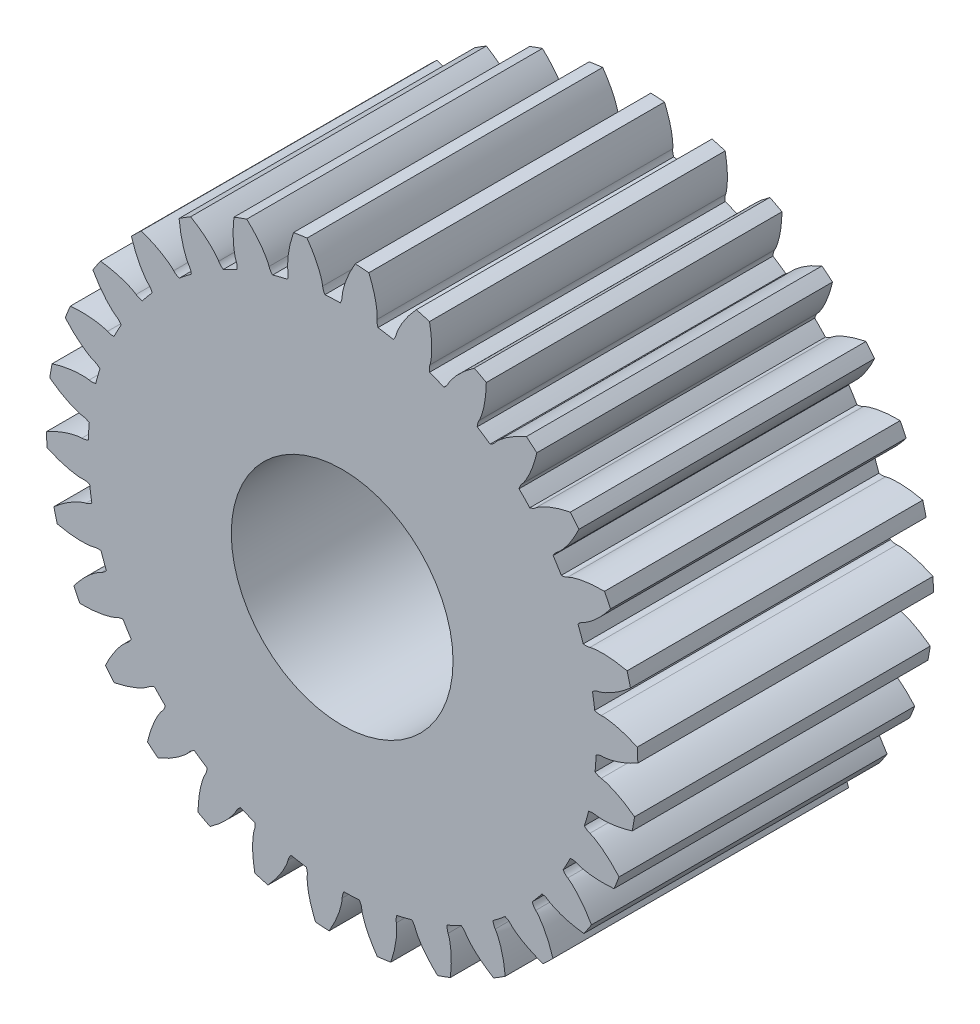
SolidWorks part; units mm, degrees
ref_plane "前视基准面" through (0, 0, 0) normal (0, 0, 1) x (1, 0, 0)
ref_plane "上视基准面" through (0, 0, 0) normal (0, 1, 0) x (1, 0, 0)
ref_plane "右视基准面" through (0, 0, 0) normal (1, 0, 0) x (0, 0, -1)
other "Configuration Table"
sketch "草图1" plane through (0, 0, 0) normal (0, 0, 1) x (1, 0, 0)
  line L0 (0, 0) -> (0.1114, 7.4992) construction
  line L1 (0, 0) -> (0.5373, 7.9819) construction
  line L3 (0, 0) -> (1.3687, 7.8821) construction
  line L5 (0.5373, 7.9819) -> (0, 0) construction
  circle A1 centre (0, 0) radius 6.875
  circle A2 centre (0, 0) radius 7.5
  circle A3 centre (0, 0) radius 8
  spline S0 degree 4 poles (0, 7.0477) (0.0001, 7.0534) (0.0009, 7.0694) (0.0038, 7.0996) (0.0108, 7.1487) (0.0229, 7.2107) (0.0421, 7.2903) (0.0695, 7.3831) (0.1044, 7.4837) (0.1475, 7.5917) (0.195, 7.6979) (0.2464, 7.8023) (0.3014, 7.9048) (0.3723, 8.027) (0.4631, 8.1708) (0.5777, 8.3344) (0.7173, 8.5146) (0.8696, 8.6918) (1.0275, 8.8608) (1.1959, 9.0248) (1.3652, 9.1787) (1.5495, 9.3312) (1.7241, 9.4682) (1.9285, 9.6131) (2.0962, 9.7275) (2.3263, 9.8688) (2.4649, 9.9494) (2.6299, 10.0402) (2.7048, 10.0787) (2.7508, 10.1025) knots 0 0 0 0 0 0.005377 0.015084 0.028532 0.04661 0.064855 0.092111 0.119476 0.146842 0.174209 0.201575 0.228941 0.256307 0.307035 0.361767 0.4165 0.471232 0.525964 0.580697 0.635429 0.690161 0.744894 0.799626 0.854358 0.909091 0.954545 1 1 1 1 1 construction
  spline S1 degree 4 poles (0, 7.0477) (0.0001, 7.0534) (0.0009, 7.0694) (0.0038, 7.0996) (0.0108, 7.1487) (0.0229, 7.2107) (0.0421, 7.2903) (0.0695, 7.3831) (0.1044, 7.4837) (0.1475, 7.5917) (0.195, 7.6979) (0.2464, 7.8023) (0.2928, 7.8887) (0.327, 7.9486) (0.3472, 7.9829) (0.3527, 7.9922) knots 0 0 0 0 0 0.005377 0.015084 0.028532 0.04661 0.064855 0.092111 0.119476 0.146842 0.174209 0.201575 0.228941 0.239097 0.239097 0.239097 0.239097 0.239097
  spline S2 degree 3 poles (0, 7.0477) (-0.0014, 6.9798) (-0.021, 6.9317) (-0.0494, 6.8748) knots 0 0 0 0 1 1 1 1
  spline S3 degree 3 poles (0.9445, 6.9841) (0.9368, 6.9167) (0.9497, 6.8664) (0.9702, 6.8062) knots 0 0 0 0 1 1 1 1
  spline S4 degree 4 poles (0.9445, 6.9841) (0.9451, 6.9898) (0.9466, 7.0058) (0.9477, 7.0361) (0.9474, 7.0856) (0.9437, 7.1488) (0.9353, 7.2302) (0.9206, 7.3258) (0.8995, 7.4302) (0.8713, 7.543) (0.8384, 7.6546) (0.8014, 7.7649) (0.7671, 7.8567) (0.7412, 7.9207) (0.7258, 7.9575) (0.7215, 7.9674) knots 0 0 0 0 0 0.005377 0.015084 0.028532 0.04661 0.064855 0.092111 0.119476 0.146842 0.174209 0.201575 0.228941 0.239097 0.239097 0.239097 0.239097 0.239097
  spline S5 degree 3 poles (1.4653, 6.8937) (1.4498, 6.8276) (1.4207, 6.7846) (1.3811, 6.7349) knots 0 0 0 0 1 1 1 1
  spline S6 degree 4 poles (1.4653, 6.8937) (1.4666, 6.8992) (1.4707, 6.9148) (1.4798, 6.9437) (1.4968, 6.9902) (1.5215, 7.0484) (1.5569, 7.1223) (1.603, 7.2073) (1.658, 7.2985) (1.7226, 7.3952) (1.7912, 7.4892) (1.8632, 7.5806) (1.9265, 7.6554) (1.9724, 7.7069) (1.9994, 7.7363) (2.0067, 7.7442) knots 0 0 0 0 0 0.005377 0.015084 0.028532 0.04661 0.064855 0.092111 0.119476 0.146842 0.174209 0.201575 0.228941 0.239097 0.239097 0.239097 0.239097 0.239097
  dimension "D1" = 15
  dimension "D2" = 16
  dimension "D3" = 13.75
  dimension "D5" = 3
  dimension "D6" = 9
sketch "草图3" plane through (0, 0, 0) normal (0, 0, 1) x (1, 0, 0)
  circle A0 centre (0, 0) radius 6.875 construction
  circle A1 centre (0, 0) radius 8 construction
  arc A2 (1.3811, 6.7349) -> (0.9702, 6.8062) centre (0, 0) ccw
  arc A3 (0.7215, 7.9674) -> (0.3527, 7.9922) centre (0, 0) ccw
  arc A4 (2.3623, 7.6433) -> (2.0067, 7.7442) centre (0, 0) ccw
  arc A5 (2.7512, 6.3005) -> (2.3641, 6.4557) centre (0, 0) ccw
  arc A6 (3.8998, 6.9851) -> (3.573, 7.1578) centre (0, 0) ccw
  arc A7 (4.001, 5.5909) -> (3.6547, 5.8231) centre (0, 0) ccw
  arc A8 (5.2669, 6.0216) -> (4.9831, 6.2585) centre (0, 0) ccw
  arc A9 (5.076, 4.6368) -> (4.7855, 4.936) centre (0, 0) ccw
  arc A10 (6.4037, 4.795) -> (6.1754, 5.0857) centre (0, 0) ccw
  arc A11 (5.9291, 3.4802) -> (5.7072, 3.8332) centre (0, 0) ccw
  arc A12 (7.2607, 3.3588) -> (7.0978, 3.6906) centre (0, 0) ccw
  arc A13 (6.5231, 2.1714) -> (6.3795, 2.5628) centre (0, 0) ccw
  arc A14 (7.8004, 1.7758) -> (7.7101, 2.1343) centre (0, 0) ccw
  arc A15 (6.832, 0.7677) -> (6.7729, 1.1805) centre (0, 0) ccw
  arc A16 (7.9992, 0.1152) -> (7.9853, 0.4846) centre (0, 0) ccw
  arc A17 (6.8423, -0.6695) -> (6.8703, -0.2535) centre (0, 0) ccw
  arc A18 (7.8483, -1.5504) -> (7.9116, -1.1862) centre (0, 0) ccw
  arc A19 (6.5536, -2.0775) -> (6.6675, -1.6764) centre (0, 0) ccw
  arc A20 (7.3545, -3.1483) -> (7.4921, -2.8052) centre (0, 0) ccw
  arc A21 (5.9785, -3.3947) -> (6.1733, -3.026) centre (0, 0) ccw
  arc A22 (6.5392, -4.6086) -> (6.7451, -4.3016) centre (0, 0) ccw
  arc A23 (5.142, -4.5635) -> (5.4092, -4.2434) centre (0, 0) ccw
  arc A24 (5.4381, -5.8674) -> (5.7034, -5.61) centre (0, 0) ccw
  arc A25 (4.0809, -5.5328) -> (4.4088, -5.2753) centre (0, 0) ccw
  arc A26 (4.0994, -6.8699) -> (4.4124, -6.6732) centre (0, 0) ccw
  arc A27 (2.8413, -6.2604) -> (3.2156, -6.0766) centre (0, 0) ccw
  arc A28 (2.5815, -7.5721) -> (2.9285, -7.4447) centre (0, 0) ccw
  arc A29 (1.4776, -6.7143) -> (1.882, -6.6124) centre (0, 0) ccw
  arc A30 (0.9507, -7.9433) -> (1.3167, -7.8909) centre (0, 0) ccw
  arc A31 (0.0494, -6.8748) -> (0.466, -6.8592) centre (0, 0) ccw
  arc A32 (-0.7215, -7.9674) -> (-0.3527, -7.9922) centre (0, 0) ccw
  arc A33 (-1.3811, -6.7349) -> (-0.9702, -6.8062) centre (0, 0) ccw
  arc A34 (-2.3623, -7.6433) -> (-2.0067, -7.7442) centre (0, 0) ccw
  arc A35 (-2.7512, -6.3005) -> (-2.3641, -6.4557) centre (0, 0) ccw
  arc A36 (-3.8998, -6.9851) -> (-3.573, -7.1578) centre (0, 0) ccw
  arc A37 (-4.001, -5.5909) -> (-3.6547, -5.8231) centre (0, 0) ccw
  arc A38 (-5.2669, -6.0216) -> (-4.9831, -6.2585) centre (0, 0) ccw
  arc A39 (-5.076, -4.6368) -> (-4.7855, -4.936) centre (0, 0) ccw
  arc A40 (-6.4037, -4.795) -> (-6.1754, -5.0857) centre (0, 0) ccw
  arc A41 (-5.9291, -3.4802) -> (-5.7072, -3.8332) centre (0, 0) ccw
  arc A42 (-7.2607, -3.3588) -> (-7.0978, -3.6906) centre (0, 0) ccw
  arc A43 (-6.5231, -2.1714) -> (-6.3795, -2.5628) centre (0, 0) ccw
  arc A44 (-7.8004, -1.7758) -> (-7.7101, -2.1343) centre (0, 0) ccw
  arc A45 (-6.832, -0.7677) -> (-6.7729, -1.1805) centre (0, 0) ccw
  arc A46 (-7.9992, -0.1152) -> (-7.9853, -0.4846) centre (0, 0) ccw
  arc A47 (-6.8423, 0.6695) -> (-6.8703, 0.2535) centre (0, 0) ccw
  arc A48 (-7.8483, 1.5504) -> (-7.9116, 1.1862) centre (0, 0) ccw
  arc A49 (-6.5536, 2.0775) -> (-6.6675, 1.6764) centre (0, 0) ccw
  arc A50 (-7.3545, 3.1483) -> (-7.4921, 2.8052) centre (0, 0) ccw
  arc A51 (-5.9785, 3.3947) -> (-6.1733, 3.026) centre (0, 0) ccw
  arc A52 (-6.5392, 4.6086) -> (-6.7451, 4.3016) centre (0, 0) ccw
  arc A53 (-5.142, 4.5635) -> (-5.4092, 4.2434) centre (0, 0) ccw
  arc A54 (-5.4381, 5.8674) -> (-5.7034, 5.61) centre (0, 0) ccw
  arc A55 (-4.0809, 5.5328) -> (-4.4088, 5.2753) centre (0, 0) ccw
  arc A56 (-4.0994, 6.8699) -> (-4.4124, 6.6732) centre (0, 0) ccw
  arc A57 (-2.8413, 6.2604) -> (-3.2156, 6.0766) centre (0, 0) ccw
  arc A58 (-2.5815, 7.5721) -> (-2.9285, 7.4447) centre (0, 0) ccw
  arc A59 (-1.4776, 6.7143) -> (-1.882, 6.6124) centre (0, 0) ccw
  arc A60 (-0.9507, 7.9433) -> (-1.3167, 7.8909) centre (0, 0) ccw
  arc A61 (-0.0494, 6.8748) -> (-0.466, 6.8592) centre (0, 0) ccw
  spline S1 degree 4 poles (1.4653, 6.8937) (1.4666, 6.8992) (1.4707, 6.9148) (1.4798, 6.9437) (1.4968, 6.9902) (1.5215, 7.0484) (1.5569, 7.1223) (1.603, 7.2073) (1.658, 7.2985) (1.7226, 7.3952) (1.7912, 7.4892) (1.8632, 7.5806) (1.9265, 7.6554) (1.9724, 7.7069) (1.9994, 7.7363) (2.0067, 7.7442) knots 0 0 0 0 0 0.005377 0.015084 0.028532 0.04661 0.064855 0.092111 0.119476 0.146842 0.174209 0.201575 0.228941 0.239097 0.239097 0.239097 0.239097 0.239097
  spline S2 degree 3 poles (-1315.1222, 3784.3622) (1264.915, -3777.2147) (-1209.7875, 3808.8549) (1149.4643, -3824.0344) knots -50.295597 -50.295597 -50.295597 -50.295597 51.921301 51.921301 51.921301 51.921301 only from (0, 7.0477) to (-0.0494, 6.8748) construction
  spline S3 degree 3 poles (1810.4204, 3573.9784) (-1759.7083, -3573.6239) (1709.3183, 3612.3665) (-1651.5736, -3635.4933) knots -50.295597 -50.295597 -50.295597 -50.295597 51.921301 51.921301 51.921301 51.921301 only from (0.9445, 6.9841) to (0.9702, 6.8062) construction
  spline S4 degree 4 poles (-3965.8718, 519.2661) (-41.989, 10.4435) (0.1579, 5.5929) (0.9525, 6.3275) (0.9474, 7.0856) (0.9437, 7.1488) (0.9353, 7.2302) (0.9206, 7.3258) (0.8995, 7.4302) (0.8713, 7.543) (0.8384, 7.6546) (0.8014, 7.7649) (-0.3454, 10.8309) (-5.2464, 12.5394) (15.5955, -0.3531) (-3224.3266, 2374.0128) knots -0.666672 -0.666672 -0.666672 -0.666672 -0.666672 0.005377 0.015084 0.028532 0.04661 0.064855 0.092111 0.119476 0.146842 0.174209 0.201575 0.228941 3.228043 3.228043 3.228043 3.228043 3.228043 only from (0.9445, 6.9841) to (0.7215, 7.9674) construction
  spline S5 degree 4 poles (3999.6863, -16.9046) (43.0098, 4.7221) (0.5931, 5.5636) (-0.096, 6.398) (0.0108, 7.1487) (0.0229, 7.2107) (0.0421, 7.2903) (0.0695, 7.3831) (0.1044, 7.4837) (0.1475, 7.5917) (0.195, 7.6979) (0.2464, 7.8023) (1.7938, 10.6869) (6.8795, 11.7232) (-15.5022, 1.7401) (3513.3944, 1920.4892) knots -0.666672 -0.666672 -0.666672 -0.666672 -0.666672 0.005377 0.015084 0.028532 0.04661 0.064855 0.092111 0.119476 0.146842 0.174209 0.201575 0.228941 3.228043 3.228043 3.228043 3.228043 3.228043 only from (0, 7.0477) to (0.3527, 7.9922) construction
  spline S6 degree 4 poles (2.3759, 6.6351) (2.3777, 6.6405) (2.3825, 6.6559) (2.3899, 6.6853) (2.3998, 6.7338) (2.4094, 6.7963) (2.4181, 6.8778) (2.4236, 6.9743) (2.4247, 7.0808) (2.4205, 7.197) (2.4116, 7.313) (2.3983, 7.4286) (2.3838, 7.5256) (2.3718, 7.5935) (2.3643, 7.6327) (2.3623, 7.6433) knots 0 0 0 0 0 0.005377 0.015084 0.028532 0.04661 0.064855 0.092111 0.119476 0.146842 0.174209 0.201575 0.228941 0.239097 0.239097 0.239097 0.239097 0.239097
  spline S7 degree 3 poles (2.3759, 6.6351) (2.3544, 6.5708) (2.3566, 6.5189) (2.3641, 6.4557) knots 0 0 0 0 1 1 1 1
  spline S8 degree 3 poles (0, 7.0477) (-0.0014, 6.9798) (-0.021, 6.9317) (-0.0494, 6.8748) knots 0 0 0 0 1 1 1 1
  spline S9 degree 3 poles (0.9445, 6.9841) (0.9368, 6.9167) (0.9497, 6.8664) (0.9702, 6.8062) knots 0 0 0 0 1 1 1 1
  spline S10 degree 4 poles (0.9445, 6.9841) (0.9451, 6.9898) (0.9466, 7.0058) (0.9477, 7.0361) (0.9474, 7.0856) (0.9437, 7.1488) (0.9353, 7.2302) (0.9206, 7.3258) (0.8995, 7.4302) (0.8713, 7.543) (0.8384, 7.6546) (0.8014, 7.7649) (0.7671, 7.8567) (0.7412, 7.9207) (0.7258, 7.9575) (0.7215, 7.9674) knots 0 0 0 0 0 0.005377 0.015084 0.028532 0.04661 0.064855 0.092111 0.119476 0.146842 0.174209 0.201575 0.228941 0.239097 0.239097 0.239097 0.239097 0.239097
  spline S11 degree 4 poles (0, 7.0477) (0.0001, 7.0534) (0.0009, 7.0694) (0.0038, 7.0996) (0.0108, 7.1487) (0.0229, 7.2107) (0.0421, 7.2903) (0.0695, 7.3831) (0.1044, 7.4837) (0.1475, 7.5917) (0.195, 7.6979) (0.2464, 7.8023) (0.2928, 7.8887) (0.327, 7.9486) (0.3472, 7.9829) (0.3527, 7.9922) knots 0 0 0 0 0 0.005377 0.015084 0.028532 0.04661 0.064855 0.092111 0.119476 0.146842 0.174209 0.201575 0.228941 0.239097 0.239097 0.239097 0.239097 0.239097
  spline S12 degree 3 poles (1.4653, 6.8937) (1.4498, 6.8276) (1.4207, 6.7846) (1.3811, 6.7349) knots 0 0 0 0 1 1 1 1
  spline S13 degree 4 poles (2.8666, 6.4384) (2.869, 6.4436) (2.8762, 6.4579) (2.8911, 6.4843) (2.9175, 6.5263) (2.9537, 6.578) (3.0037, 6.6429) (3.0664, 6.7165) (3.1393, 6.7943) (3.2225, 6.8754) (3.3091, 6.9531) (3.3986, 7.0275) (3.4761, 7.0876) (3.5317, 7.1284) (3.5641, 7.1516) (3.573, 7.1578) knots 0 0 0 0 0 0.005377 0.015084 0.028532 0.04661 0.064855 0.092111 0.119476 0.146842 0.174209 0.201575 0.228941 0.239097 0.239097 0.239097 0.239097 0.239097
  spline S14 degree 4 poles (3.7035, 5.9961) (3.7064, 6.0011) (3.7142, 6.0151) (3.7276, 6.0423) (3.7474, 6.0877) (3.7698, 6.1469) (3.7952, 6.2247) (3.8207, 6.318) (3.8439, 6.422) (3.864, 6.5365) (3.8794, 6.6518) (3.8904, 6.7677) (3.8964, 6.8655) (3.8988, 6.9344) (3.8996, 6.9743) (3.8998, 6.9851) knots 0 0 0 0 0 0.005377 0.015084 0.028532 0.04661 0.064855 0.092111 0.119476 0.146842 0.174209 0.201575 0.228941 0.239097 0.239097 0.239097 0.239097 0.239097
  spline S15 degree 3 poles (3.7035, 5.9961) (3.6691, 5.9377) (3.6604, 5.8864) (3.6547, 5.8231) knots 0 0 0 0 1 1 1 1
  spline S16 degree 3 poles (2.8666, 6.4384) (2.8376, 6.377) (2.8002, 6.341) (2.7512, 6.3005) knots 0 0 0 0 1 1 1 1
  spline S17 degree 4 poles (4.1425, 5.7017) (4.146, 5.7063) (4.156, 5.7188) (4.1761, 5.7415) (4.2106, 5.7771) (4.2569, 5.8202) (4.3192, 5.8732) (4.3959, 5.9322) (4.4833, 5.9931) (4.5816, 6.0551) (4.6824, 6.1132) (4.7854, 6.1673) (4.8737, 6.21) (4.9366, 6.2384) (4.9732, 6.2543) (4.9831, 6.2585) knots 0 0 0 0 0 0.005377 0.015084 0.028532 0.04661 0.064855 0.092111 0.119476 0.146842 0.174209 0.201575 0.228941 0.239097 0.239097 0.239097 0.239097 0.239097
  spline S18 degree 4 poles (4.8693, 5.0951) (4.8731, 5.0993) (4.8837, 5.1114) (4.9024, 5.1353) (4.9313, 5.1755) (4.9654, 5.2288) (5.0065, 5.2996) (5.0508, 5.3856) (5.0951, 5.4825) (5.1385, 5.5903) (5.1776, 5.6999) (5.2125, 5.8109) (5.2386, 5.9054) (5.2553, 5.9723) (5.2644, 6.0111) (5.2669, 6.0216) knots 0 0 0 0 0 0.005377 0.015084 0.028532 0.04661 0.064855 0.092111 0.119476 0.146842 0.174209 0.201575 0.228941 0.239097 0.239097 0.239097 0.239097 0.239097
  spline S19 degree 3 poles (4.8693, 5.0951) (4.8234, 5.0451) (4.8043, 4.9968) (4.7855, 4.936) knots 0 0 0 0 1 1 1 1
  spline S20 degree 3 poles (4.1425, 5.7017) (4.1015, 5.6477) (4.0574, 5.6202) (4.001, 5.5909) knots 0 0 0 0 1 1 1 1
  spline S21 degree 4 poles (5.2375, 4.7158) (5.2418, 4.7196) (5.2542, 4.7297) (5.2786, 4.7478) (5.3197, 4.7754) (5.3739, 4.8079) (5.4459, 4.8469) (5.5332, 4.8886) (5.6313, 4.93) (5.7404, 4.9703) (5.8511, 5.006) (5.9631, 5.0376) (6.0583, 5.061) (6.1257, 5.0757) (6.1648, 5.0836) (6.1754, 5.0857) knots 0 0 0 0 0 0.005377 0.015084 0.028532 0.04661 0.064855 0.092111 0.119476 0.146842 0.174209 0.201575 0.228941 0.239097 0.239097 0.239097 0.239097 0.239097
  spline S22 degree 4 poles (5.8222, 3.9714) (5.8269, 3.9747) (5.8397, 3.9843) (5.863, 4.0038) (5.8996, 4.0372) (5.944, 4.0821) (5.9989, 4.1429) (6.0601, 4.2178) (6.1236, 4.3033) (6.1885, 4.3998) (6.2495, 4.4988) (6.3067, 4.6002) (6.352, 4.6871) (6.3822, 4.7491) (6.3992, 4.7852) (6.4037, 4.795) knots 0 0 0 0 0 0.005377 0.015084 0.028532 0.04661 0.064855 0.092111 0.119476 0.146842 0.174209 0.201575 0.228941 0.239097 0.239097 0.239097 0.239097 0.239097
  spline S23 degree 3 poles (5.8222, 3.9714) (5.767, 3.932) (5.7382, 3.8887) (5.7072, 3.8332) knots 0 0 0 0 1 1 1 1
  spline S24 degree 3 poles (5.2375, 4.7158) (5.1861, 4.6715) (5.1372, 4.6538) (5.076, 4.6368) knots 0 0 0 0 1 1 1 1
  spline S25 degree 4 poles (6.1035, 3.5238) (6.1085, 3.5266) (6.1227, 3.534) (6.1503, 3.5465) (6.1963, 3.565) (6.2561, 3.5856) (6.3347, 3.6087) (6.4287, 3.6314) (6.5333, 3.6515) (6.6483, 3.6681) (6.7641, 3.6801) (6.8802, 3.6877) (6.9782, 3.6908) (7.0472, 3.6911) (7.087, 3.6908) (7.0978, 3.6906) knots 0 0 0 0 0 0.005377 0.015084 0.028532 0.04661 0.064855 0.092111 0.119476 0.146842 0.174209 0.201575 0.228941 0.239097 0.239097 0.239097 0.239097 0.239097
  spline S26 degree 4 poles (6.5207, 2.6741) (6.5259, 2.6764) (6.5405, 2.6831) (6.5673, 2.6973) (6.61, 2.7224) (6.6629, 2.7571) (6.7292, 2.8051) (6.8046, 2.8656) (6.8845, 2.9361) (6.9681, 3.017) (7.0483, 3.1012) (7.1253, 3.1884) (7.1877, 3.2641) (7.2301, 3.3184) (7.2542, 3.3502) (7.2607, 3.3588) knots 0 0 0 0 0 0.005377 0.015084 0.028532 0.04661 0.064855 0.092111 0.119476 0.146842 0.174209 0.201575 0.228941 0.239097 0.239097 0.239097 0.239097 0.239097
  spline S27 degree 3 poles (6.5207, 2.6741) (6.4585, 2.647) (6.4213, 2.6107) (6.3795, 2.5628) knots 0 0 0 0 1 1 1 1
  spline S28 degree 3 poles (6.1035, 3.5238) (6.044, 3.4912) (5.9925, 3.484) (5.9291, 3.4802) knots 0 0 0 0 1 1 1 1
  spline S29 degree 4 poles (6.7028, 2.1779) (6.7082, 2.1795) (6.7237, 2.1838) (6.7533, 2.1903) (6.8021, 2.1988) (6.8649, 2.2065) (6.9465, 2.2128) (7.0432, 2.2154) (7.1497, 2.2133) (7.2657, 2.2057) (7.3814, 2.1934) (7.4966, 2.1767) (7.593, 2.1593) (7.6606, 2.1453) (7.6995, 2.1367) (7.7101, 2.1343) knots 0 0 0 0 0 0.005377 0.015084 0.028532 0.04661 0.064855 0.092111 0.119476 0.146842 0.174209 0.201575 0.228941 0.239097 0.239097 0.239097 0.239097 0.239097
  spline S30 degree 4 poles (6.9342, 1.2599) (6.9398, 1.2611) (6.9554, 1.2647) (6.9846, 1.273) (7.0316, 1.2886) (7.0905, 1.3116) (7.1653, 1.3448) (7.2517, 1.3883) (7.3445, 1.4406) (7.443, 1.5023) (7.539, 1.568) (7.6325, 1.6373) (7.7092, 1.6983) (7.7621, 1.7427) (7.7923, 1.7688) (7.8004, 1.7758) knots 0 0 0 0 0 0.005377 0.015084 0.028532 0.04661 0.064855 0.092111 0.119476 0.146842 0.174209 0.201575 0.228941 0.239097 0.239097 0.239097 0.239097 0.239097
  spline S31 degree 3 poles (6.9342, 1.2599) (6.8677, 1.2464) (6.8238, 1.2186) (6.7729, 1.1805) knots 0 0 0 0 1 1 1 1
  spline S32 degree 3 poles (6.7028, 2.1779) (6.6378, 2.1583) (6.586, 2.162) (6.5231, 2.1714) knots 0 0 0 0 1 1 1 1
  spline S33 degree 4 poles (7.0091, 0.7367) (7.0148, 0.7372) (7.0308, 0.7381) (7.0611, 0.7383) (7.1106, 0.7365) (7.1736, 0.731) (7.2548, 0.7202) (7.3499, 0.7026) (7.4536, 0.6785) (7.5655, 0.6469) (7.6761, 0.6108) (7.7853, 0.5705) (7.876, 0.5334) (7.9392, 0.5057) (7.9755, 0.4891) (7.9853, 0.4846) knots 0 0 0 0 0 0.005377 0.015084 0.028532 0.04661 0.064855 0.092111 0.119476 0.146842 0.174209 0.201575 0.228941 0.239097 0.239097 0.239097 0.239097 0.239097
  spline S34 degree 4 poles (7.0446, -0.2093) (7.0503, -0.2093) (7.0663, -0.2091) (7.0966, -0.207) (7.1458, -0.2015) (7.2082, -0.1913) (7.2884, -0.1744) (7.3819, -0.1498) (7.4835, -0.1179) (7.5927, -0.078) (7.7003, -0.0337) (7.8062, 0.0146) (7.8939, 0.0584) (7.9548, 0.0908) (7.9897, 0.11) (7.9992, 0.1152) knots 0 0 0 0 0 0.005377 0.015084 0.028532 0.04661 0.064855 0.092111 0.119476 0.146842 0.174209 0.201575 0.228941 0.239097 0.239097 0.239097 0.239097 0.239097
  spline S35 degree 3 poles (7.0446, -0.2093) (6.9767, -0.2087) (6.928, -0.2268) (6.8703, -0.2535) knots 0 0 0 0 1 1 1 1
  spline S36 degree 3 poles (7.0091, 0.7367) (6.9415, 0.731) (6.8915, 0.7454) (6.832, 0.7677) knots 0 0 0 0 1 1 1 1
  spline S37 degree 4 poles (7.0091, -0.7367) (7.0148, -0.7374) (7.0306, -0.7398) (7.0603, -0.7459) (7.1084, -0.7579) (7.1689, -0.7765) (7.246, -0.8039) (7.3354, -0.8408) (7.4318, -0.8861) (7.5347, -0.9402) (7.6354, -0.9985) (7.7338, -1.0607) (7.8148, -1.1158) (7.8709, -1.156) (7.9029, -1.1798) (7.9116, -1.1862) knots 0 0 0 0 0 0.005377 0.015084 0.028532 0.04661 0.064855 0.092111 0.119476 0.146842 0.174209 0.201575 0.228941 0.239097 0.239097 0.239097 0.239097 0.239097
  spline S38 degree 4 poles (6.8471, -1.6694) (6.8527, -1.6706) (6.8684, -1.6737) (6.8985, -1.678) (6.9478, -1.6828) (7.011, -1.6858) (7.0928, -1.6859) (7.1894, -1.6813) (7.2955, -1.6712) (7.4106, -1.655) (7.525, -1.634) (7.6386, -1.6087) (7.7335, -1.5841) (7.7998, -1.5651) (7.838, -1.5536) (7.8483, -1.5504) knots 0 0 0 0 0 0.005377 0.015084 0.028532 0.04661 0.064855 0.092111 0.119476 0.146842 0.174209 0.201575 0.228941 0.239097 0.239097 0.239097 0.239097 0.239097
  spline S39 degree 3 poles (6.8471, -1.6694) (6.7809, -1.6547) (6.7295, -1.6623) (6.6675, -1.6764) knots 0 0 0 0 1 1 1 1
  spline S40 degree 3 poles (7.0091, -0.7367) (6.9418, -0.7282) (6.8959, -0.7037) (6.8423, -0.6695) knots 0 0 0 0 1 1 1 1
  spline S41 degree 4 poles (6.7028, -2.1779) (6.7082, -2.1797) (6.7232, -2.1854) (6.751, -2.1975) (6.7955, -2.2193) (6.8508, -2.25) (6.9205, -2.2929) (7.0002, -2.3476) (7.0852, -2.4119) (7.1746, -2.4862) (7.2609, -2.5642) (7.3443, -2.6454) (7.4121, -2.7162) (7.4585, -2.7672) (7.4849, -2.7971) (7.4921, -2.8052) knots 0 0 0 0 0 0.005377 0.015084 0.028532 0.04661 0.064855 0.092111 0.119476 0.146842 0.174209 0.201575 0.228941 0.239097 0.239097 0.239097 0.239097 0.239097
  spline S42 degree 4 poles (6.3504, -3.0565) (6.3556, -3.0589) (6.3704, -3.0651) (6.3989, -3.0756) (6.4461, -3.0906) (6.5073, -3.1066) (6.5873, -3.1237) (6.6827, -3.1393) (6.7886, -3.1515) (6.9046, -3.1595) (7.0209, -3.1628) (7.1372, -3.1617) (7.2352, -3.1574) (7.304, -3.1526) (7.3437, -3.1492) (7.3545, -3.1483) knots 0 0 0 0 0 0.005377 0.015084 0.028532 0.04661 0.064855 0.092111 0.119476 0.146842 0.174209 0.201575 0.228941 0.239097 0.239097 0.239097 0.239097 0.239097
  spline S43 degree 3 poles (6.3504, -3.0565) (6.2887, -3.0284) (6.2368, -3.0251) (6.1733, -3.026) knots 0 0 0 0 1 1 1 1
  spline S44 degree 3 poles (6.7028, -2.1779) (6.6387, -2.1555) (6.5989, -2.1221) (6.5536, -2.0775) knots 0 0 0 0 1 1 1 1
  spline S45 degree 4 poles (6.1035, -3.5238) (6.1084, -3.5268) (6.1219, -3.5355) (6.1466, -3.5531) (6.1855, -3.5837) (6.2333, -3.6252) (6.2925, -3.6816) (6.3592, -3.7517) (6.4289, -3.8323) (6.5009, -3.9236) (6.5691, -4.0178) (6.6338, -4.1146) (6.6854, -4.1979) (6.7202, -4.2574) (6.7398, -4.2922) (6.7451, -4.3016) knots 0 0 0 0 0 0.005377 0.015084 0.028532 0.04661 0.064855 0.092111 0.119476 0.146842 0.174209 0.201575 0.228941 0.239097 0.239097 0.239097 0.239097 0.239097
  spline S46 degree 4 poles (5.5762, -4.31) (5.5808, -4.3134) (5.5939, -4.3226) (5.6196, -4.3388) (5.6627, -4.3633) (5.7192, -4.3917) (5.7939, -4.4251) (5.884, -4.4601) (5.985, -4.4941) (6.0968, -4.526) (6.2099, -4.5534) (6.3239, -4.5765) (6.4206, -4.5927) (6.4889, -4.6023) (6.5285, -4.6073) (6.5392, -4.6086) knots 0 0 0 0 0 0.005377 0.015084 0.028532 0.04661 0.064855 0.092111 0.119476 0.146842 0.174209 0.201575 0.228941 0.239097 0.239097 0.239097 0.239097 0.239097
  spline S47 degree 3 poles (5.5762, -4.31) (5.5216, -4.2697) (5.4716, -4.2557) (5.4092, -4.2434) knots 0 0 0 0 1 1 1 1
  spline S48 degree 3 poles (6.1035, -3.5238) (6.0455, -3.4887) (6.0135, -3.4477) (5.9785, -3.3947) knots 0 0 0 0 1 1 1 1
  spline S49 degree 4 poles (5.2375, -4.7158) (5.2416, -4.7197) (5.253, -4.731) (5.2735, -4.7534) (5.3053, -4.7914) (5.3433, -4.8419) (5.3896, -4.9095) (5.4402, -4.9919) (5.4917, -5.0852) (5.5431, -5.1894) (5.5902, -5.2958) (5.6333, -5.4039) (5.6665, -5.4961) (5.6882, -5.5616) (5.7002, -5.5997) (5.7034, -5.61) knots 0 0 0 0 0 0.005377 0.015084 0.028532 0.04661 0.064855 0.092111 0.119476 0.146842 0.174209 0.201575 0.228941 0.239097 0.239097 0.239097 0.239097 0.239097
  spline S50 degree 4 poles (4.5582, -5.3752) (4.562, -5.3795) (4.5729, -5.3912) (4.5947, -5.4123) (4.6317, -5.4452) (4.6811, -5.4848) (4.7473, -5.533) (4.8281, -5.586) (4.9198, -5.6402) (5.0225, -5.6947) (5.1274, -5.745) (5.2342, -5.7913) (5.3254, -5.8272) (5.3903, -5.8508) (5.4279, -5.8639) (5.4381, -5.8674) knots 0 0 0 0 0 0.005377 0.015084 0.028532 0.04661 0.064855 0.092111 0.119476 0.146842 0.174209 0.201575 0.228941 0.239097 0.239097 0.239097 0.239097 0.239097
  spline S51 degree 3 poles (4.5582, -5.3752) (4.5132, -5.3244) (4.4672, -5.3003) (4.4088, -5.2753) knots 0 0 0 0 1 1 1 1
  spline S52 degree 3 poles (5.2375, -4.7158) (5.188, -4.6694) (5.1653, -4.6226) (5.142, -4.5635) knots 0 0 0 0 1 1 1 1
  spline S53 degree 4 poles (4.1425, -5.7017) (4.1458, -5.7064) (4.1546, -5.7198) (4.17, -5.7459) (4.1932, -5.7897) (4.2199, -5.847) (4.2511, -5.9228) (4.2834, -6.0139) (4.3144, -6.1158) (4.343, -6.2285) (4.367, -6.3423) (4.3867, -6.457) (4.4, -6.5541) (4.4075, -6.6227) (4.4114, -6.6624) (4.4124, -6.6732) knots 0 0 0 0 0 0.005377 0.015084 0.028532 0.04661 0.064855 0.092111 0.119476 0.146842 0.174209 0.201575 0.228941 0.239097 0.239097 0.239097 0.239097 0.239097
  spline S54 degree 4 poles (3.341, -6.2054) (3.3439, -6.2104) (3.3521, -6.2242) (3.369, -6.2494) (3.3984, -6.2892) (3.4385, -6.3382) (3.4932, -6.3991) (3.5612, -6.4678) (3.6397, -6.5399) (3.7288, -6.6145) (3.8209, -6.6855) (3.9158, -6.753) (3.9975, -6.8071) (4.056, -6.8437) (4.0901, -6.8643) (4.0994, -6.8699) knots 0 0 0 0 0 0.005377 0.015084 0.028532 0.04661 0.064855 0.092111 0.119476 0.146842 0.174209 0.201575 0.228941 0.239097 0.239097 0.239097 0.239097 0.239097
  spline S55 degree 3 poles (3.341, -6.2054) (3.3076, -6.1464) (3.2676, -6.1133) (3.2156, -6.0766) knots 0 0 0 0 1 1 1 1
  spline S56 degree 3 poles (4.1425, -5.7017) (4.1038, -5.646) (4.0913, -5.5955) (4.0809, -5.5328) knots 0 0 0 0 1 1 1 1
  spline S57 degree 4 poles (2.8666, -6.4384) (2.8688, -6.4437) (2.8746, -6.4586) (2.8842, -6.4874) (2.8978, -6.535) (2.912, -6.5966) (2.9268, -6.6772) (2.9395, -6.773) (2.9486, -6.8792) (2.9531, -6.9954) (2.9529, -7.1117) (2.9483, -7.228) (2.9411, -7.3257) (2.9343, -7.3944) (2.9298, -7.434) (2.9285, -7.4447) knots 0 0 0 0 0 0.005377 0.015084 0.028532 0.04661 0.064855 0.092111 0.119476 0.146842 0.174209 0.201575 0.228941 0.239097 0.239097 0.239097 0.239097 0.239097
  spline S58 degree 4 poles (1.9779, -6.7645) (1.9796, -6.7699) (1.9848, -6.7851) (1.9961, -6.8132) (2.0165, -6.8584) (2.0455, -6.9146) (2.0864, -6.9855) (2.1387, -7.0669) (2.2004, -7.1537) (2.2721, -7.2452) (2.3475, -7.3338) (2.4262, -7.4196) (2.4949, -7.4895) (2.5445, -7.5374) (2.5736, -7.5647) (2.5815, -7.5721) knots 0 0 0 0 0 0.005377 0.015084 0.028532 0.04661 0.064855 0.092111 0.119476 0.146842 0.174209 0.201575 0.228941 0.239097 0.239097 0.239097 0.239097 0.239097
  spline S59 degree 3 poles (1.9779, -6.7645) (1.9574, -6.6998) (1.9252, -6.659) (1.882, -6.6124) knots 0 0 0 0 1 1 1 1
  spline S60 degree 3 poles (2.8666, -6.4384) (2.8403, -6.3758) (2.8385, -6.3239) (2.8413, -6.2604) knots 0 0 0 0 1 1 1 1
  spline S61 degree 4 poles (1.4653, -6.8937) (1.4664, -6.8993) (1.469, -6.9151) (1.4724, -6.9453) (1.4758, -6.9947) (1.4768, -7.0579) (1.4745, -7.1398) (1.4671, -7.2362) (1.4539, -7.3419) (1.4342, -7.4565) (1.4098, -7.5702) (1.3811, -7.683) (1.3538, -7.7771) (1.3328, -7.8429) (1.3201, -7.8807) (1.3167, -7.8909) knots 0 0 0 0 0 0.005377 0.015084 0.028532 0.04661 0.064855 0.092111 0.119476 0.146842 0.174209 0.201575 0.228941 0.239097 0.239097 0.239097 0.239097 0.239097
  spline S62 degree 4 poles (0.5282, -7.0279) (0.5288, -7.0336) (0.5307, -7.0495) (0.5359, -7.0794) (0.5465, -7.1278) (0.5632, -7.1888) (0.5884, -7.2667) (0.6226, -7.3571) (0.665, -7.4549) (0.716, -7.5593) (0.7714, -7.6616) (0.8305, -7.7619) (0.8832, -7.8445) (0.9218, -7.9017) (0.9446, -7.9345) (0.9507, -7.9433) knots 0 0 0 0 0 0.005377 0.015084 0.028532 0.04661 0.064855 0.092111 0.119476 0.146842 0.174209 0.201575 0.228941 0.239097 0.239097 0.239097 0.239097 0.239097
  spline S63 degree 3 poles (0.5282, -7.0279) (0.5217, -6.9603) (0.4986, -6.9138) (0.466, -6.8592) knots 0 0 0 0 1 1 1 1
  spline S64 degree 3 poles (1.4653, -6.8937) (1.4526, -6.827) (1.4617, -6.7759) (1.4776, -6.7143) knots 0 0 0 0 1 1 1 1
  spline S65 degree 4 poles (0, -7.0477) (-0.0001, -7.0534) (-0.0009, -7.0694) (-0.0038, -7.0996) (-0.0108, -7.1487) (-0.0229, -7.2107) (-0.0421, -7.2903) (-0.0695, -7.3831) (-0.1044, -7.4837) (-0.1475, -7.5917) (-0.195, -7.6979) (-0.2464, -7.8023) (-0.2928, -7.8887) (-0.327, -7.9486) (-0.3472, -7.9829) (-0.3527, -7.9922) knots 0 0 0 0 0 0.005377 0.015084 0.028532 0.04661 0.064855 0.092111 0.119476 0.146842 0.174209 0.201575 0.228941 0.239097 0.239097 0.239097 0.239097 0.239097
  spline S66 degree 4 poles (-0.9445, -6.9841) (-0.9451, -6.9898) (-0.9466, -7.0058) (-0.9477, -7.0361) (-0.9474, -7.0856) (-0.9437, -7.1488) (-0.9353, -7.2302) (-0.9206, -7.3258) (-0.8995, -7.4302) (-0.8713, -7.543) (-0.8384, -7.6546) (-0.8014, -7.7649) (-0.7671, -7.8567) (-0.7412, -7.9207) (-0.7258, -7.9575) (-0.7215, -7.9674) knots 0 0 0 0 0 0.005377 0.015084 0.028532 0.04661 0.064855 0.092111 0.119476 0.146842 0.174209 0.201575 0.228941 0.239097 0.239097 0.239097 0.239097 0.239097
  spline S67 degree 3 poles (-0.9445, -6.9841) (-0.9368, -6.9167) (-0.9497, -6.8664) (-0.9702, -6.8062) knots 0 0 0 0 1 1 1 1
  spline S68 degree 3 poles (0, -7.0477) (0.0014, -6.9798) (0.021, -6.9317) (0.0494, -6.8748) knots 0 0 0 0 1 1 1 1
  spline S69 degree 4 poles (-1.4653, -6.8937) (-1.4666, -6.8992) (-1.4707, -6.9148) (-1.4798, -6.9437) (-1.4968, -6.9902) (-1.5215, -7.0484) (-1.5569, -7.1223) (-1.603, -7.2073) (-1.658, -7.2985) (-1.7226, -7.3952) (-1.7912, -7.4892) (-1.8632, -7.5806) (-1.9265, -7.6554) (-1.9724, -7.7069) (-1.9994, -7.7363) (-2.0067, -7.7442) knots 0 0 0 0 0 0.005377 0.015084 0.028532 0.04661 0.064855 0.092111 0.119476 0.146842 0.174209 0.201575 0.228941 0.239097 0.239097 0.239097 0.239097 0.239097
  spline S70 degree 4 poles (-2.3759, -6.6351) (-2.3777, -6.6405) (-2.3825, -6.6559) (-2.3899, -6.6853) (-2.3998, -6.7338) (-2.4094, -6.7963) (-2.4181, -6.8778) (-2.4236, -6.9743) (-2.4247, -7.0808) (-2.4205, -7.197) (-2.4116, -7.313) (-2.3983, -7.4286) (-2.3838, -7.5256) (-2.3718, -7.5935) (-2.3643, -7.6327) (-2.3623, -7.6433) knots 0 0 0 0 0 0.005377 0.015084 0.028532 0.04661 0.064855 0.092111 0.119476 0.146842 0.174209 0.201575 0.228941 0.239097 0.239097 0.239097 0.239097 0.239097
  spline S71 degree 3 poles (-2.3759, -6.6351) (-2.3544, -6.5708) (-2.3566, -6.5189) (-2.3641, -6.4557) knots 0 0 0 0 1 1 1 1
  spline S72 degree 3 poles (-1.4653, -6.8937) (-1.4498, -6.8276) (-1.4207, -6.7846) (-1.3811, -6.7349) knots 0 0 0 0 1 1 1 1
  spline S73 degree 4 poles (-2.8666, -6.4384) (-2.869, -6.4436) (-2.8762, -6.4579) (-2.8911, -6.4843) (-2.9175, -6.5263) (-2.9537, -6.578) (-3.0037, -6.6429) (-3.0664, -6.7165) (-3.1393, -6.7943) (-3.2225, -6.8754) (-3.3091, -6.9531) (-3.3986, -7.0275) (-3.4761, -7.0876) (-3.5317, -7.1284) (-3.5641, -7.1516) (-3.573, -7.1578) knots 0 0 0 0 0 0.005377 0.015084 0.028532 0.04661 0.064855 0.092111 0.119476 0.146842 0.174209 0.201575 0.228941 0.239097 0.239097 0.239097 0.239097 0.239097
  spline S74 degree 4 poles (-3.7035, -5.9961) (-3.7064, -6.0011) (-3.7142, -6.0151) (-3.7276, -6.0423) (-3.7474, -6.0877) (-3.7698, -6.1469) (-3.7952, -6.2247) (-3.8207, -6.318) (-3.8439, -6.422) (-3.864, -6.5365) (-3.8794, -6.6518) (-3.8904, -6.7677) (-3.8964, -6.8655) (-3.8988, -6.9344) (-3.8996, -6.9743) (-3.8998, -6.9851) knots 0 0 0 0 0 0.005377 0.015084 0.028532 0.04661 0.064855 0.092111 0.119476 0.146842 0.174209 0.201575 0.228941 0.239097 0.239097 0.239097 0.239097 0.239097
  spline S75 degree 3 poles (-3.7035, -5.9961) (-3.6691, -5.9377) (-3.6604, -5.8864) (-3.6547, -5.8231) knots 0 0 0 0 1 1 1 1
  spline S76 degree 3 poles (-2.8666, -6.4384) (-2.8376, -6.377) (-2.8002, -6.341) (-2.7512, -6.3005) knots 0 0 0 0 1 1 1 1
  spline S77 degree 4 poles (-4.1425, -5.7017) (-4.146, -5.7063) (-4.156, -5.7188) (-4.1761, -5.7415) (-4.2106, -5.7771) (-4.2569, -5.8202) (-4.3192, -5.8732) (-4.3959, -5.9322) (-4.4833, -5.9931) (-4.5816, -6.0551) (-4.6824, -6.1132) (-4.7854, -6.1673) (-4.8737, -6.21) (-4.9366, -6.2384) (-4.9732, -6.2543) (-4.9831, -6.2585) knots 0 0 0 0 0 0.005377 0.015084 0.028532 0.04661 0.064855 0.092111 0.119476 0.146842 0.174209 0.201575 0.228941 0.239097 0.239097 0.239097 0.239097 0.239097
  spline S78 degree 4 poles (-4.8693, -5.0951) (-4.8731, -5.0993) (-4.8837, -5.1114) (-4.9024, -5.1353) (-4.9313, -5.1755) (-4.9654, -5.2288) (-5.0065, -5.2996) (-5.0508, -5.3856) (-5.0951, -5.4825) (-5.1385, -5.5903) (-5.1776, -5.6999) (-5.2125, -5.8109) (-5.2386, -5.9054) (-5.2553, -5.9723) (-5.2644, -6.0111) (-5.2669, -6.0216) knots 0 0 0 0 0 0.005377 0.015084 0.028532 0.04661 0.064855 0.092111 0.119476 0.146842 0.174209 0.201575 0.228941 0.239097 0.239097 0.239097 0.239097 0.239097
  spline S79 degree 3 poles (-4.8693, -5.0951) (-4.8234, -5.0451) (-4.8043, -4.9968) (-4.7855, -4.936) knots 0 0 0 0 1 1 1 1
  spline S80 degree 3 poles (-4.1425, -5.7017) (-4.1015, -5.6477) (-4.0574, -5.6202) (-4.001, -5.5909) knots 0 0 0 0 1 1 1 1
  spline S81 degree 4 poles (-5.2375, -4.7158) (-5.2418, -4.7196) (-5.2542, -4.7297) (-5.2786, -4.7478) (-5.3197, -4.7754) (-5.3739, -4.8079) (-5.4459, -4.8469) (-5.5332, -4.8886) (-5.6313, -4.93) (-5.7404, -4.9703) (-5.8511, -5.006) (-5.9631, -5.0376) (-6.0583, -5.061) (-6.1257, -5.0757) (-6.1648, -5.0836) (-6.1754, -5.0857) knots 0 0 0 0 0 0.005377 0.015084 0.028532 0.04661 0.064855 0.092111 0.119476 0.146842 0.174209 0.201575 0.228941 0.239097 0.239097 0.239097 0.239097 0.239097
  spline S82 degree 4 poles (-5.8222, -3.9714) (-5.8269, -3.9747) (-5.8397, -3.9843) (-5.863, -4.0038) (-5.8996, -4.0372) (-5.944, -4.0821) (-5.9989, -4.1429) (-6.0601, -4.2178) (-6.1236, -4.3033) (-6.1885, -4.3998) (-6.2495, -4.4988) (-6.3067, -4.6002) (-6.352, -4.6871) (-6.3822, -4.7491) (-6.3992, -4.7852) (-6.4037, -4.795) knots 0 0 0 0 0 0.005377 0.015084 0.028532 0.04661 0.064855 0.092111 0.119476 0.146842 0.174209 0.201575 0.228941 0.239097 0.239097 0.239097 0.239097 0.239097
  spline S83 degree 3 poles (-5.8222, -3.9714) (-5.767, -3.932) (-5.7382, -3.8887) (-5.7072, -3.8332) knots 0 0 0 0 1 1 1 1
  spline S84 degree 3 poles (-5.2375, -4.7158) (-5.1861, -4.6715) (-5.1372, -4.6538) (-5.076, -4.6368) knots 0 0 0 0 1 1 1 1
  spline S85 degree 4 poles (-6.1035, -3.5238) (-6.1085, -3.5266) (-6.1227, -3.534) (-6.1503, -3.5465) (-6.1963, -3.565) (-6.2561, -3.5856) (-6.3347, -3.6087) (-6.4287, -3.6314) (-6.5333, -3.6515) (-6.6483, -3.6681) (-6.7641, -3.6801) (-6.8802, -3.6877) (-6.9782, -3.6908) (-7.0472, -3.6911) (-7.087, -3.6908) (-7.0978, -3.6906) knots 0 0 0 0 0 0.005377 0.015084 0.028532 0.04661 0.064855 0.092111 0.119476 0.146842 0.174209 0.201575 0.228941 0.239097 0.239097 0.239097 0.239097 0.239097
  spline S86 degree 4 poles (-6.5207, -2.6741) (-6.5259, -2.6764) (-6.5405, -2.6831) (-6.5673, -2.6973) (-6.61, -2.7224) (-6.6629, -2.7571) (-6.7292, -2.8051) (-6.8046, -2.8656) (-6.8845, -2.9361) (-6.9681, -3.017) (-7.0483, -3.1012) (-7.1253, -3.1884) (-7.1877, -3.2641) (-7.2301, -3.3184) (-7.2542, -3.3502) (-7.2607, -3.3588) knots 0 0 0 0 0 0.005377 0.015084 0.028532 0.04661 0.064855 0.092111 0.119476 0.146842 0.174209 0.201575 0.228941 0.239097 0.239097 0.239097 0.239097 0.239097
  spline S87 degree 3 poles (-6.5207, -2.6741) (-6.4585, -2.647) (-6.4213, -2.6107) (-6.3795, -2.5628) knots 0 0 0 0 1 1 1 1
  spline S88 degree 3 poles (-6.1035, -3.5238) (-6.044, -3.4912) (-5.9925, -3.484) (-5.9291, -3.4802) knots 0 0 0 0 1 1 1 1
  spline S89 degree 4 poles (-6.7028, -2.1779) (-6.7082, -2.1795) (-6.7237, -2.1838) (-6.7533, -2.1903) (-6.8021, -2.1988) (-6.8649, -2.2065) (-6.9465, -2.2128) (-7.0432, -2.2154) (-7.1497, -2.2133) (-7.2657, -2.2057) (-7.3814, -2.1934) (-7.4966, -2.1767) (-7.593, -2.1593) (-7.6606, -2.1453) (-7.6995, -2.1367) (-7.7101, -2.1343) knots 0 0 0 0 0 0.005377 0.015084 0.028532 0.04661 0.064855 0.092111 0.119476 0.146842 0.174209 0.201575 0.228941 0.239097 0.239097 0.239097 0.239097 0.239097
  spline S90 degree 4 poles (-6.9342, -1.2599) (-6.9398, -1.2611) (-6.9554, -1.2647) (-6.9846, -1.273) (-7.0316, -1.2886) (-7.0905, -1.3116) (-7.1653, -1.3448) (-7.2517, -1.3883) (-7.3445, -1.4406) (-7.443, -1.5023) (-7.539, -1.568) (-7.6325, -1.6373) (-7.7092, -1.6983) (-7.7621, -1.7427) (-7.7923, -1.7688) (-7.8004, -1.7758) knots 0 0 0 0 0 0.005377 0.015084 0.028532 0.04661 0.064855 0.092111 0.119476 0.146842 0.174209 0.201575 0.228941 0.239097 0.239097 0.239097 0.239097 0.239097
  spline S91 degree 3 poles (-6.9342, -1.2599) (-6.8677, -1.2464) (-6.8238, -1.2186) (-6.7729, -1.1805) knots 0 0 0 0 1 1 1 1
  spline S92 degree 3 poles (-6.7028, -2.1779) (-6.6378, -2.1583) (-6.586, -2.162) (-6.5231, -2.1714) knots 0 0 0 0 1 1 1 1
  spline S93 degree 4 poles (-7.0091, -0.7367) (-7.0148, -0.7372) (-7.0308, -0.7381) (-7.0611, -0.7383) (-7.1106, -0.7365) (-7.1736, -0.731) (-7.2548, -0.7202) (-7.3499, -0.7026) (-7.4536, -0.6785) (-7.5655, -0.6469) (-7.6761, -0.6108) (-7.7853, -0.5705) (-7.876, -0.5334) (-7.9392, -0.5057) (-7.9755, -0.4891) (-7.9853, -0.4846) knots 0 0 0 0 0 0.005377 0.015084 0.028532 0.04661 0.064855 0.092111 0.119476 0.146842 0.174209 0.201575 0.228941 0.239097 0.239097 0.239097 0.239097 0.239097
  spline S94 degree 4 poles (-7.0446, 0.2093) (-7.0503, 0.2093) (-7.0663, 0.2091) (-7.0966, 0.207) (-7.1458, 0.2015) (-7.2082, 0.1913) (-7.2884, 0.1744) (-7.3819, 0.1498) (-7.4835, 0.1179) (-7.5927, 0.078) (-7.7003, 0.0337) (-7.8062, -0.0146) (-7.8939, -0.0584) (-7.9548, -0.0908) (-7.9897, -0.11) (-7.9992, -0.1152) knots 0 0 0 0 0 0.005377 0.015084 0.028532 0.04661 0.064855 0.092111 0.119476 0.146842 0.174209 0.201575 0.228941 0.239097 0.239097 0.239097 0.239097 0.239097
  spline S95 degree 3 poles (-7.0446, 0.2093) (-6.9767, 0.2087) (-6.928, 0.2268) (-6.8703, 0.2535) knots 0 0 0 0 1 1 1 1
  spline S96 degree 3 poles (-7.0091, -0.7367) (-6.9415, -0.731) (-6.8915, -0.7454) (-6.832, -0.7677) knots 0 0 0 0 1 1 1 1
  spline S97 degree 4 poles (-7.0091, 0.7367) (-7.0148, 0.7374) (-7.0306, 0.7398) (-7.0603, 0.7459) (-7.1084, 0.7579) (-7.1689, 0.7765) (-7.246, 0.8039) (-7.3354, 0.8408) (-7.4318, 0.8861) (-7.5347, 0.9402) (-7.6354, 0.9985) (-7.7338, 1.0607) (-7.8148, 1.1158) (-7.8709, 1.156) (-7.9029, 1.1798) (-7.9116, 1.1862) knots 0 0 0 0 0 0.005377 0.015084 0.028532 0.04661 0.064855 0.092111 0.119476 0.146842 0.174209 0.201575 0.228941 0.239097 0.239097 0.239097 0.239097 0.239097
  spline S98 degree 4 poles (-6.8471, 1.6694) (-6.8527, 1.6706) (-6.8684, 1.6737) (-6.8985, 1.678) (-6.9478, 1.6828) (-7.011, 1.6858) (-7.0928, 1.6859) (-7.1894, 1.6813) (-7.2955, 1.6712) (-7.4106, 1.655) (-7.525, 1.634) (-7.6386, 1.6087) (-7.7335, 1.5841) (-7.7998, 1.5651) (-7.838, 1.5536) (-7.8483, 1.5504) knots 0 0 0 0 0 0.005377 0.015084 0.028532 0.04661 0.064855 0.092111 0.119476 0.146842 0.174209 0.201575 0.228941 0.239097 0.239097 0.239097 0.239097 0.239097
  spline S99 degree 3 poles (-6.8471, 1.6694) (-6.7809, 1.6547) (-6.7295, 1.6623) (-6.6675, 1.6764) knots 0 0 0 0 1 1 1 1
  spline S100 degree 3 poles (-7.0091, 0.7367) (-6.9418, 0.7282) (-6.8959, 0.7037) (-6.8423, 0.6695) knots 0 0 0 0 1 1 1 1
  spline S101 degree 4 poles (-6.7028, 2.1779) (-6.7082, 2.1797) (-6.7232, 2.1854) (-6.751, 2.1975) (-6.7955, 2.2193) (-6.8508, 2.25) (-6.9205, 2.2929) (-7.0002, 2.3476) (-7.0852, 2.4119) (-7.1746, 2.4862) (-7.2609, 2.5642) (-7.3443, 2.6454) (-7.4121, 2.7162) (-7.4585, 2.7672) (-7.4849, 2.7971) (-7.4921, 2.8052) knots 0 0 0 0 0 0.005377 0.015084 0.028532 0.04661 0.064855 0.092111 0.119476 0.146842 0.174209 0.201575 0.228941 0.239097 0.239097 0.239097 0.239097 0.239097
  spline S102 degree 4 poles (-6.3504, 3.0565) (-6.3556, 3.0589) (-6.3704, 3.0651) (-6.3989, 3.0756) (-6.4461, 3.0906) (-6.5073, 3.1066) (-6.5873, 3.1237) (-6.6827, 3.1393) (-6.7886, 3.1515) (-6.9046, 3.1595) (-7.0209, 3.1628) (-7.1372, 3.1617) (-7.2352, 3.1574) (-7.304, 3.1526) (-7.3437, 3.1492) (-7.3545, 3.1483) knots 0 0 0 0 0 0.005377 0.015084 0.028532 0.04661 0.064855 0.092111 0.119476 0.146842 0.174209 0.201575 0.228941 0.239097 0.239097 0.239097 0.239097 0.239097
  spline S103 degree 3 poles (-6.3504, 3.0565) (-6.2887, 3.0284) (-6.2368, 3.0251) (-6.1733, 3.026) knots 0 0 0 0 1 1 1 1
  spline S104 degree 3 poles (-6.7028, 2.1779) (-6.6387, 2.1555) (-6.5989, 2.1221) (-6.5536, 2.0775) knots 0 0 0 0 1 1 1 1
  spline S105 degree 4 poles (-6.1035, 3.5238) (-6.1084, 3.5268) (-6.1219, 3.5355) (-6.1466, 3.5531) (-6.1855, 3.5837) (-6.2333, 3.6252) (-6.2925, 3.6816) (-6.3592, 3.7517) (-6.4289, 3.8323) (-6.5009, 3.9236) (-6.5691, 4.0178) (-6.6338, 4.1146) (-6.6854, 4.1979) (-6.7202, 4.2574) (-6.7398, 4.2922) (-6.7451, 4.3016) knots 0 0 0 0 0 0.005377 0.015084 0.028532 0.04661 0.064855 0.092111 0.119476 0.146842 0.174209 0.201575 0.228941 0.239097 0.239097 0.239097 0.239097 0.239097
  spline S106 degree 4 poles (-5.5762, 4.31) (-5.5808, 4.3134) (-5.5939, 4.3226) (-5.6196, 4.3388) (-5.6627, 4.3633) (-5.7192, 4.3917) (-5.7939, 4.4251) (-5.884, 4.4601) (-5.985, 4.4941) (-6.0968, 4.526) (-6.2099, 4.5534) (-6.3239, 4.5765) (-6.4206, 4.5927) (-6.4889, 4.6023) (-6.5285, 4.6073) (-6.5392, 4.6086) knots 0 0 0 0 0 0.005377 0.015084 0.028532 0.04661 0.064855 0.092111 0.119476 0.146842 0.174209 0.201575 0.228941 0.239097 0.239097 0.239097 0.239097 0.239097
  spline S107 degree 3 poles (-5.5762, 4.31) (-5.5216, 4.2697) (-5.4716, 4.2557) (-5.4092, 4.2434) knots 0 0 0 0 1 1 1 1
  spline S108 degree 3 poles (-6.1035, 3.5238) (-6.0455, 3.4887) (-6.0135, 3.4477) (-5.9785, 3.3947) knots 0 0 0 0 1 1 1 1
  spline S109 degree 4 poles (-5.2375, 4.7158) (-5.2416, 4.7197) (-5.253, 4.731) (-5.2735, 4.7534) (-5.3053, 4.7914) (-5.3433, 4.8419) (-5.3896, 4.9095) (-5.4402, 4.9919) (-5.4917, 5.0852) (-5.5431, 5.1894) (-5.5902, 5.2958) (-5.6333, 5.4039) (-5.6665, 5.4961) (-5.6882, 5.5616) (-5.7002, 5.5997) (-5.7034, 5.61) knots 0 0 0 0 0 0.005377 0.015084 0.028532 0.04661 0.064855 0.092111 0.119476 0.146842 0.174209 0.201575 0.228941 0.239097 0.239097 0.239097 0.239097 0.239097
  spline S110 degree 4 poles (-4.5582, 5.3752) (-4.562, 5.3795) (-4.5729, 5.3912) (-4.5947, 5.4123) (-4.6317, 5.4452) (-4.6811, 5.4848) (-4.7473, 5.533) (-4.8281, 5.586) (-4.9198, 5.6402) (-5.0225, 5.6947) (-5.1274, 5.745) (-5.2342, 5.7913) (-5.3254, 5.8272) (-5.3903, 5.8508) (-5.4279, 5.8639) (-5.4381, 5.8674) knots 0 0 0 0 0 0.005377 0.015084 0.028532 0.04661 0.064855 0.092111 0.119476 0.146842 0.174209 0.201575 0.228941 0.239097 0.239097 0.239097 0.239097 0.239097
  spline S111 degree 3 poles (-4.5582, 5.3752) (-4.5132, 5.3244) (-4.4672, 5.3003) (-4.4088, 5.2753) knots 0 0 0 0 1 1 1 1
  spline S112 degree 3 poles (-5.2375, 4.7158) (-5.188, 4.6694) (-5.1653, 4.6226) (-5.142, 4.5635) knots 0 0 0 0 1 1 1 1
  spline S113 degree 4 poles (-4.1425, 5.7017) (-4.1458, 5.7064) (-4.1546, 5.7198) (-4.17, 5.7459) (-4.1932, 5.7897) (-4.2199, 5.847) (-4.2511, 5.9228) (-4.2834, 6.0139) (-4.3144, 6.1158) (-4.343, 6.2285) (-4.367, 6.3423) (-4.3867, 6.457) (-4.4, 6.5541) (-4.4075, 6.6227) (-4.4114, 6.6624) (-4.4124, 6.6732) knots 0 0 0 0 0 0.005377 0.015084 0.028532 0.04661 0.064855 0.092111 0.119476 0.146842 0.174209 0.201575 0.228941 0.239097 0.239097 0.239097 0.239097 0.239097
  spline S114 degree 4 poles (-3.341, 6.2054) (-3.3439, 6.2104) (-3.3521, 6.2242) (-3.369, 6.2494) (-3.3984, 6.2892) (-3.4385, 6.3382) (-3.4932, 6.3991) (-3.5612, 6.4678) (-3.6397, 6.5399) (-3.7288, 6.6145) (-3.8209, 6.6855) (-3.9158, 6.753) (-3.9975, 6.8071) (-4.056, 6.8437) (-4.0901, 6.8643) (-4.0994, 6.8699) knots 0 0 0 0 0 0.005377 0.015084 0.028532 0.04661 0.064855 0.092111 0.119476 0.146842 0.174209 0.201575 0.228941 0.239097 0.239097 0.239097 0.239097 0.239097
  spline S115 degree 3 poles (-3.341, 6.2054) (-3.3076, 6.1464) (-3.2676, 6.1133) (-3.2156, 6.0766) knots 0 0 0 0 1 1 1 1
  spline S116 degree 3 poles (-4.1425, 5.7017) (-4.1038, 5.646) (-4.0913, 5.5955) (-4.0809, 5.5328) knots 0 0 0 0 1 1 1 1
  spline S117 degree 4 poles (-2.8666, 6.4384) (-2.8688, 6.4437) (-2.8746, 6.4586) (-2.8842, 6.4874) (-2.8978, 6.535) (-2.912, 6.5966) (-2.9268, 6.6772) (-2.9395, 6.773) (-2.9486, 6.8792) (-2.9531, 6.9954) (-2.9529, 7.1117) (-2.9483, 7.228) (-2.9411, 7.3257) (-2.9343, 7.3944) (-2.9298, 7.434) (-2.9285, 7.4447) knots 0 0 0 0 0 0.005377 0.015084 0.028532 0.04661 0.064855 0.092111 0.119476 0.146842 0.174209 0.201575 0.228941 0.239097 0.239097 0.239097 0.239097 0.239097
  spline S118 degree 4 poles (-1.9779, 6.7645) (-1.9796, 6.7699) (-1.9848, 6.7851) (-1.9961, 6.8132) (-2.0165, 6.8584) (-2.0455, 6.9146) (-2.0864, 6.9855) (-2.1387, 7.0669) (-2.2004, 7.1537) (-2.2721, 7.2452) (-2.3475, 7.3338) (-2.4262, 7.4196) (-2.4949, 7.4895) (-2.5445, 7.5374) (-2.5736, 7.5647) (-2.5815, 7.5721) knots 0 0 0 0 0 0.005377 0.015084 0.028532 0.04661 0.064855 0.092111 0.119476 0.146842 0.174209 0.201575 0.228941 0.239097 0.239097 0.239097 0.239097 0.239097
  spline S119 degree 3 poles (-1.9779, 6.7645) (-1.9574, 6.6998) (-1.9252, 6.659) (-1.882, 6.6124) knots 0 0 0 0 1 1 1 1
  spline S120 degree 3 poles (-2.8666, 6.4384) (-2.8403, 6.3758) (-2.8385, 6.3239) (-2.8413, 6.2604) knots 0 0 0 0 1 1 1 1
  spline S121 degree 4 poles (-1.4653, 6.8937) (-1.4664, 6.8993) (-1.469, 6.9151) (-1.4724, 6.9453) (-1.4758, 6.9947) (-1.4768, 7.0579) (-1.4745, 7.1398) (-1.4671, 7.2362) (-1.4539, 7.3419) (-1.4342, 7.4565) (-1.4098, 7.5702) (-1.3811, 7.683) (-1.3538, 7.7771) (-1.3328, 7.8429) (-1.3201, 7.8807) (-1.3167, 7.8909) knots 0 0 0 0 0 0.005377 0.015084 0.028532 0.04661 0.064855 0.092111 0.119476 0.146842 0.174209 0.201575 0.228941 0.239097 0.239097 0.239097 0.239097 0.239097
  spline S122 degree 4 poles (-0.5282, 7.0279) (-0.5288, 7.0336) (-0.5307, 7.0495) (-0.5359, 7.0794) (-0.5465, 7.1278) (-0.5632, 7.1888) (-0.5884, 7.2667) (-0.6226, 7.3571) (-0.665, 7.4549) (-0.716, 7.5593) (-0.7714, 7.6616) (-0.8305, 7.7619) (-0.8832, 7.8445) (-0.9218, 7.9017) (-0.9446, 7.9345) (-0.9507, 7.9433) knots 0 0 0 0 0 0.005377 0.015084 0.028532 0.04661 0.064855 0.092111 0.119476 0.146842 0.174209 0.201575 0.228941 0.239097 0.239097 0.239097 0.239097 0.239097
  spline S123 degree 3 poles (-0.5282, 7.0279) (-0.5217, 6.9603) (-0.4986, 6.9138) (-0.466, 6.8592) knots 0 0 0 0 1 1 1 1
  spline S124 degree 3 poles (-1.4653, 6.8937) (-1.4526, 6.827) (-1.4617, 6.7759) (-1.4776, 6.7143) knots 0 0 0 0 1 1 1 1
  point P217 (0, 0)
  dimension "D1" = 30
extrude "凸台-拉伸1" add sketch "草图3" along normal blind 8
sketch "草图4" plane through (0, 0, 8) normal (0, 0, 1) x (1, 0, 0)
  circle A0 centre (0, 0) radius 3
  dimension "D1" = 6
extrude "切除-拉伸1" cut sketch "草图4" against normal through all
